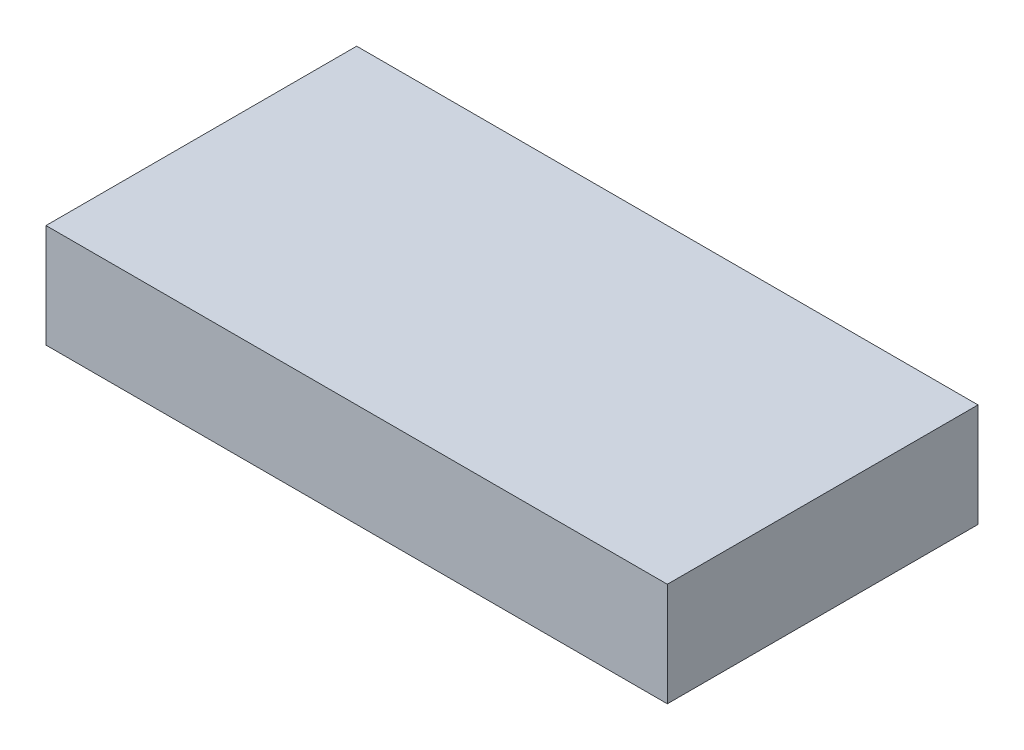
SolidWorks part; units mm, degrees
ref_plane "Front Plane" through (0, 0, 0) normal (0, 0, 1) x (1, 0, 0)
ref_plane "Top Plane" through (0, 0, 0) normal (0, 1, 0) x (1, 0, 0)
ref_plane "Right Plane" through (0, 0, 0) normal (1, 0, 0) x (0, 0, -1)
sketch "Sketch1" plane through (0, 0, 0) normal (0, 1, 0) x (1, 0, 0)
  line L1 (-12, 6) -> (12, 6)
  line L2 (-12, 6) -> (-12, -6)
  line L3 (-12, -6) -> (12, -6)
  line L4 (12, 6) -> (12, -6)
  line L5 (-12, 6) -> (12, -6) construction
  line L6 (-12, -6) -> (12, 6) construction
  point P0 (0, 0)
  dimension "D1" = 24
  dimension "D2" = 12
extrude "Boss-Extrude1" add sketch "Sketch1" along normal blind 4
sketch "Sketch2" plane through (0, 4, 0) normal (0, 1, 0) x (1, 0, 0)
  line L0 (0, 6) -> (0, -6) construction
  line L1 (12, 6) -> (-12, 6) construction
  line L2 (-12, -6) -> (12, -6) construction
  line L3 (-12, -2) -> (12, -2) construction
  line L4 (-12, 6) -> (-12, -6) construction
  line L5 (12, -6) -> (12, 6) construction
  circle A0 centre (-6, -2) radius 1.5
  circle A1 centre (6, -2) radius 1.5
  dimension "D1" = 3
  dimension "D2" = 12
  dimension "D3" = 2
